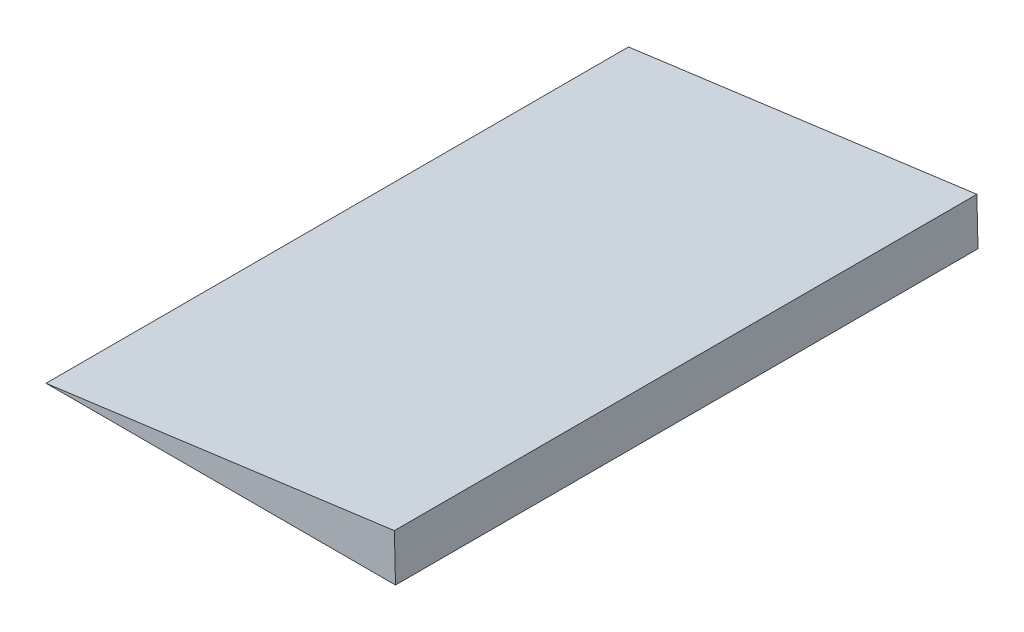
SolidWorks part; units mm, degrees
ref_plane "Front Plane" through (0, 0, 0) normal (0, 0, 1) x (1, 0, 0)
ref_plane "Top Plane" through (0, 0, 0) normal (0, 1, 0) x (1, 0, 0)
ref_plane "Right Plane" through (0, 0, 0) normal (1, 0, 0) x (0, 0, -1)
sketch "Sketch1" plane through (0, 0, 0) normal (0, 0, 1) x (1, 0, 0)
  line L0 (0, 0) -> (-499.8558, 0) construction
  line L1 (0, 0) -> (50, 0)
  line L2 (0, 0) -> (0, 44)
  line L3 (0, 44) -> (50, 44)
  line L4 (50, 0) -> (50, 44)
  line L5 (-499.8558, 0) -> (-500.6243, 31.9908)
  line L6 (-500.6243, 31.9908) -> (-0.7686, 44)
  line L7 (-499.8558, 0) -> (0, 12.0092)
  line L8 (0, 12.0092) -> (-0.7686, 44)
  line L9 (-500.3361, 19.9942) -> (-0.4804, 32.0035)
  line L10 (0, 32) -> (50, 32)
  line L11 (0, 12) -> (50, 12)
  dimension "D1" = 44
  dimension "D2" = 50
  dimension "D3" = 32
  dimension "D4" = 500
  dimension "D5" = 20
  dimension "D6" = 32
  dimension "D7" = 12
sketch "Sketch2" plane through (0, 0, 0) normal (0, 0, 1) x (1, 0, 0)
  line L0 (0, 12) -> (-40, 11.0482)
  line L1 (-499.8558, 0) -> (0, 12.0092) construction
  line L2 (-40, 11.0482) -> (-40, 0)
  line L3 (0, 0) -> (-499.8558, 0) construction
  line L4 (-40, 0) -> (0, 0)
  line L5 (0, 0) -> (0, 12)
  dimension "D1" = 40
sketch "Sketch3" plane through (0, 0, 0) normal (0, 0, 1) x (1, 0, 0)
  line L0 (-39.9885, 11.0485) -> (-40.4688, 31.0427)
  line L1 (-499.8558, 0) -> (0, 12.0092) construction
  line L2 (-500.3361, 19.9942) -> (-0.4804, 32.0035) construction
  line L3 (-40.4688, 31.0427) -> (-0.4804, 32.0035)
  line L4 (-0.4804, 32.0035) -> (39.5196, 32)
  line L5 (0, 32) -> (50, 32) construction
  line L7 (0, 12) -> (50, 12) construction
  line L8 (39.5196, 12) -> (0, 12)
  line L9 (0, 12) -> (-39.9885, 11.0485)
  line L10 (-40.2286, 21.0456) -> (-0.2402, 22.0063) construction
  line L11 (0, 12.0092) -> (-0.7686, 44) construction
  line L12 (39.5196, 32) -> (39.5196, 12)
  line L13 (39.5196, 22) -> (0, 22) construction
  line L14 (0, 0) -> (0, 44) construction
  circle A0 centre (19.7598, 22) radius 2.2
  circle A1 centre (-20.2344, 21.526) radius 2.2
  dimension "D3" = 4.4
  dimension "D1" = 40
  dimension "D2" = 40
sketch "Sketch4" plane through (0, 0, 0) normal (0, 0, 1) x (1, 0, 0)
  line L0 (-499.8558, 0) -> (-769.6838, 0) construction
  line L1 (-500.3361, 19.9942) -> (-649.8558, 0)
  line L2 (-649.8558, 0) -> (-499.8558, 0)
  line L3 (-499.8558, 0) -> (-500.3361, 19.9942)
  dimension "D1" = 150
extrude "Boss-Extrude1" add sketch "Sketch4" against normal blind 250
